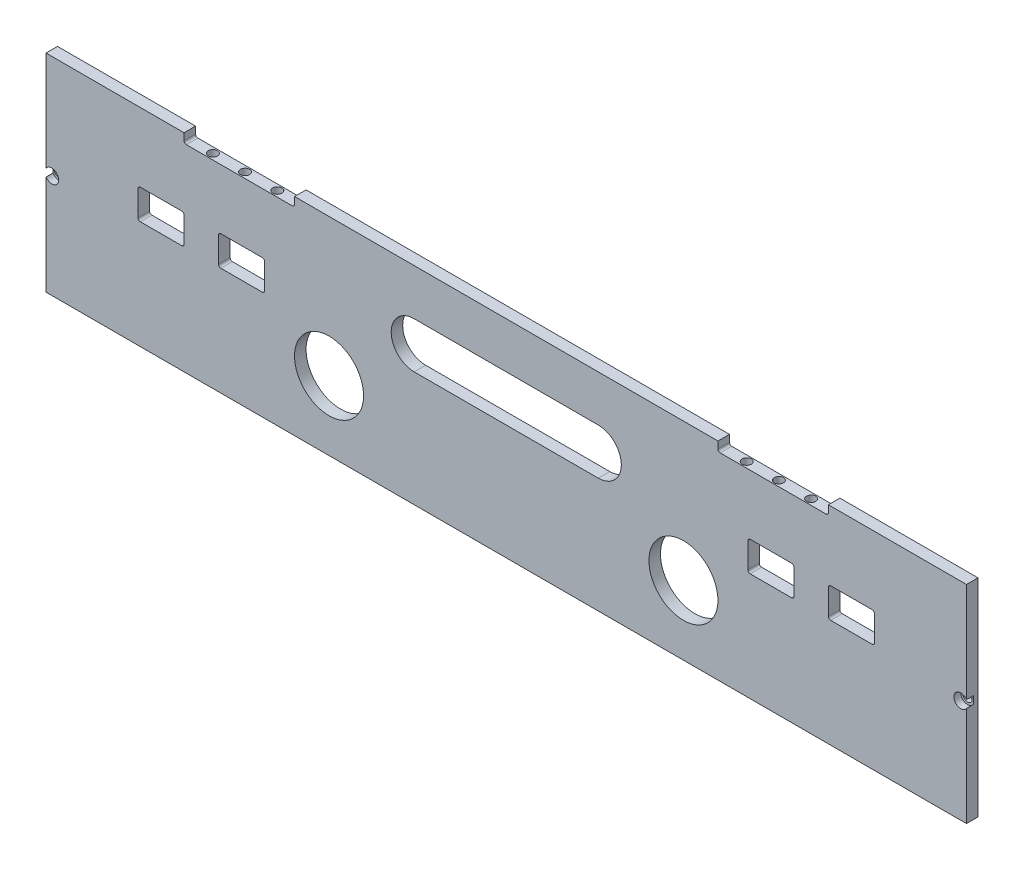
SolidWorks part; units mm, degrees
ref_plane "Front Plane" through (0, 0, 0) normal (0, 0, 1) x (1, 0, 0)
ref_plane "Top Plane" through (0, 0, 0) normal (0, 1, 0) x (1, 0, 0)
ref_plane "Right Plane" through (0, 0, 0) normal (1, 0, 0) x (0, 0, -1)
sketch "Sketch1" plane through (0, 0, 0) normal (0, 0, 1) x (1, 0, 0)
  line L0 (160, 60) -> (240, 60) construction
  line L1 (0, 0) -> (400, 0)
  line L2 (0, 0) -> (0, 90)
  line L3 (0, 90) -> (400, 90)
  line L4 (400, 0) -> (400, 90)
  line L5 (60, 90) -> (108, 90)
  line L6 (60, 90) -> (60, 86)
  line L7 (60, 86) -> (108, 86)
  line L8 (108, 90) -> (108, 86)
  line L9 (292, 90) -> (340, 90)
  line L10 (292, 90) -> (292, 86)
  line L11 (292, 86) -> (340, 86)
  line L12 (340, 90) -> (340, 86)
  line L13 (160, 70) -> (240, 70)
  line L14 (160, 50) -> (240, 50)
  line L16 (40, 60) -> (60, 60)
  line L17 (40, 60) -> (40, 47)
  line L18 (40, 47) -> (60, 47)
  line L19 (60, 60) -> (60, 47)
  line L20 (75, 60) -> (95, 60)
  line L21 (75, 60) -> (75, 47)
  line L22 (75, 47) -> (95, 47)
  line L23 (95, 60) -> (95, 47)
  line L24 (305, 60) -> (325, 60)
  line L25 (305, 60) -> (305, 47)
  line L26 (305, 47) -> (325, 47)
  line L27 (325, 60) -> (325, 47)
  line L28 (340, 60) -> (360, 60)
  line L29 (340, 60) -> (340, 47)
  line L30 (340, 47) -> (360, 47)
  line L31 (360, 60) -> (360, 47)
  arc A0 (160, 70) -> (160, 50) centre (160, 60) ccw
  arc A1 (240, 50) -> (240, 70) centre (240, 60) ccw
  circle A2 centre (2.5, 45) radius 2
  circle A3 centre (397.5, 45) radius 2
  circle A5 centre (123, 30) radius 15
  circle A6 centre (277, 30) radius 15
  point P15 (200, 60)
  dimension "D9" = 160
  dimension "D11" = 2.5
  dimension "D12" = 2.5
  dimension "D13" = 45
  dimension "D14" = 45
  dimension "D15" = 20
  dimension "D30" = 30
  dimension "D32" = 123
  dimension "D1" = 90
  dimension "D2" = 400
  dimension "D3" = 60
  dimension "D4" = 60
  dimension "D5" = 48
  dimension "D6" = 48
  dimension "D7" = 4
  dimension "D8" = 4
  dimension "D10" = 30
  dimension "D16" = 13
  dimension "D17" = 30
  dimension "D18" = 20
  dimension "D19" = 13
  dimension "D20" = 13
  dimension "D21" = 13
  dimension "D22" = 20
  dimension "D23" = 20
  dimension "D24" = 30
  dimension "D25" = 30
  dimension "D26" = 40
  dimension "D27" = 15
  dimension "D28" = 40
  dimension "D29" = 15
  dimension "D31" = 123
  dimension "D33" = 30
extrude "Boss-Extrude1" add sketch "Sketch1" along normal blind 5 contours L3 L12 L11 L10 L8 L7 L6 L2 L1 L4 A3 A2 A1 L14 A0 L13
sketch "Sketch6" plane through (0, 0, 5) normal (0, 0, 1) x (1, 0, 0)
  circle A0 centre (2.5, 45) radius 3
  circle A1 centre (397.5, 45) radius 3
  circle M2 centre (397.5, 45) radius 2
  circle M3 centre (2.5, 45) radius 2
extrude "Cut-Extrude2" cut sketch "Sketch6" against normal blind 3 contours A1 M2 | A0 M3
fillet "Fillet1" radius 1 20 edges at (292, 86, 2.5) (340, 86, 2.5) (108, 86, 2.5) (60, 86, 2.5) (325, 60, 2.5) (360, 60, 2.5) (340, 60, 2.5) (305, 60, 2.5) (305, 47, 2.5) (340, 47, 2.5) (360, 47, 2.5) (325, 47, 2.5) (95, 47, 2.5) (60, 47, 2.5) (75, 47, 2.5) (40, 47, 2.5) (75, 60, 2.5) (95, 60, 2.5) (60, 60, 2.5) (40, 60, 2.5)
sketch "Sketch7" plane through (0, 0, 0) normal (0, -1, 0) x (1, 0, 0)
  line L0 (400, 5) -> (400, 0) construction
  line L1 (0, 5) -> (400, 5) construction
  line L2 (0, 5) -> (0, 0) construction
  circle A0 centre (40, 2.5) radius 1.25
  circle A1 centre (360, 2.5) radius 1.25
  dimension "D1" = 40
  dimension "D2" = 2.5
  dimension "D3" = 2.5
  dimension "D4" = 40
extrude "Cut-Extrude3" cut sketch "Sketch7" against normal blind 15 contours A1 | A0
sketch "Sketch8" plane through (0, 86, 0) normal (0, 1, 0) x (1, 0, 0)
  line L0 (0, -5) -> (0, 0) construction
  line L1 (61, 0) -> (107, 0) construction
  circle A0 centre (70, -2.5) radius 2
  circle A1 centre (84, -2.5) radius 2
  circle A2 centre (98, -2.5) radius 2
  dimension "D1" = 70
  dimension "D2" = 14
  dimension "D3" = 28
  dimension "D4" = 2.5
sketch "Sketch9" plane through (0, 86, 0) normal (0, 1, 0) x (1, 0, 0)
  line L0 (400, -5) -> (400, 0) construction
  line L1 (293, 0) -> (339, 0) construction
  circle A0 centre (330, -2.5) radius 2
  circle A1 centre (316, -2.5) radius 2
  circle A2 centre (302, -2.5) radius 2
  dimension "D1" = 70
  dimension "D2" = 14
  dimension "D3" = 28
  dimension "D4" = 2.5
extrude "Cut-Extrude4" cut sketch "Sketch9" against normal blind 8
extrude "Cut-Extrude5" cut sketch "Sketch8" against normal blind 8 contours A0 | A1 | A2
